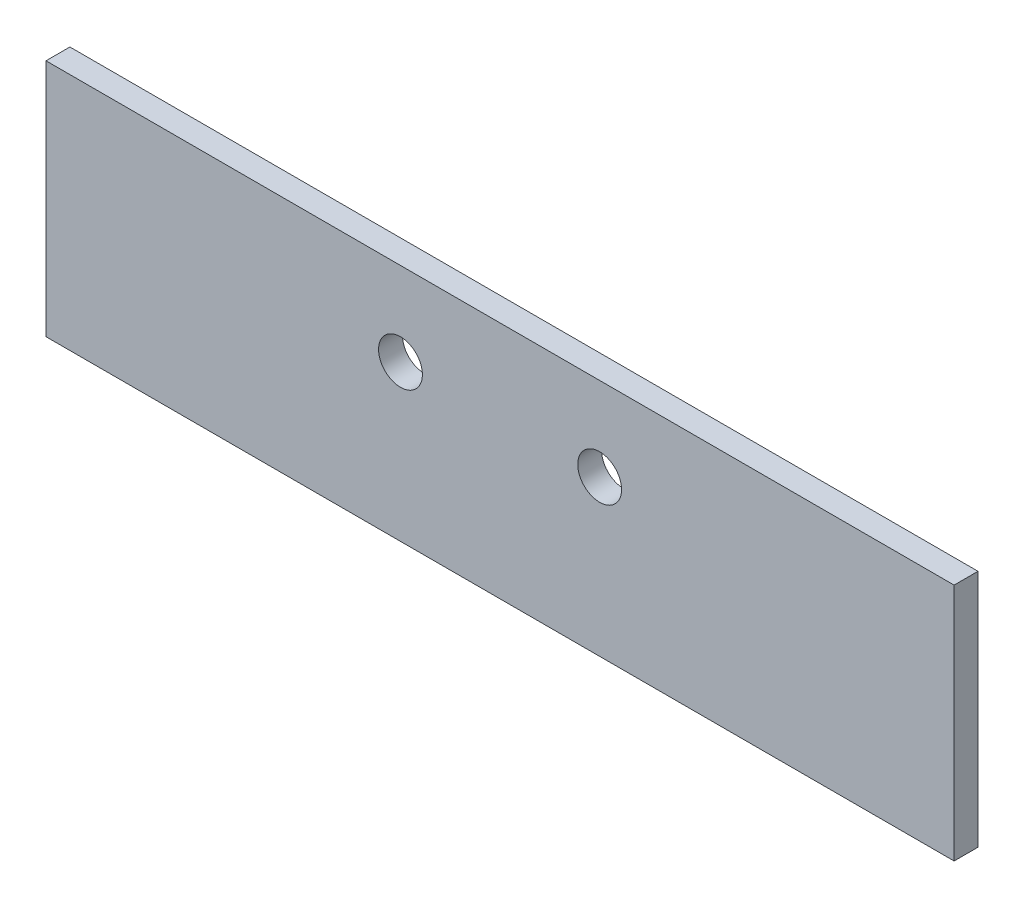
SolidWorks part; units mm, degrees
ref_plane "Front Plane" through (0, 0, 0) normal (0, 0, 1) x (1, 0, 0)
ref_plane "Top Plane" through (0, 0, 0) normal (0, 1, 0) x (1, 0, 0)
ref_plane "Right Plane" through (0, 0, 0) normal (1, 0, 0) x (0, 0, -1)
sketch "Sketch1" plane through (0, 0, 0) normal (0, 0, 1) x (1, 0, 0)
  line L1 (57, 15) -> (-57, 15)
  line L2 (57, 15) -> (57, -15)
  line L3 (57, -15) -> (-57, -15)
  line L4 (-57, 15) -> (-57, -15)
  line L5 (57, 15) -> (-57, -15) construction
  line L6 (57, -15) -> (-57, 15) construction
  point P0 (0, 0)
  dimension "D1" = 30
  dimension "D2" = 114
extrude "Boss-Extrude1" add sketch "Sketch1" along normal mid plane 3
sketch "Sketch2" plane through (0, 0, 1.5) normal (0, 0, 1) x (1, 0, 0)
  line L0 (0, 33.9142) -> (0, -42.3967) construction
  line L1 (-12.5, 4.5) -> (12.5, 4.5) construction
  line L3 (57, 15) -> (-57, 15) construction
  point P3 (-12.5, 4.5)
  point P4 (12.5, 4.5)
  point P9 (12.5, 4.5)
  point P10 (-12.5, 4.5)
  point P11 (0, 4.5)
  dimension "D1" = 25
  dimension "D3" = 10.5
hole_wizard "M5 Clearance Hole1" positions "Sketch2" profile "Sketch3" hole size "M5" standard "ISO" end condition through all
sketch "Sketch3" plane through (-12.5, 4.5, 1.5) normal (1, 0, 0) x (0, -1, 0)
  line L0 (0, 0) -> (0, 3)
  line L1 (0, 3) -> (2.75, 3)
  line L2 (2.75, 3) -> (2.75, 0)
  line L5 (2.75, 0) -> (0, 0)
  line L11 (0, -6.35) -> (0, 107.95) construction
  dimension "Thru Hole Dia." = 5.5
  dimension "Thru Hole Depth" = 3
